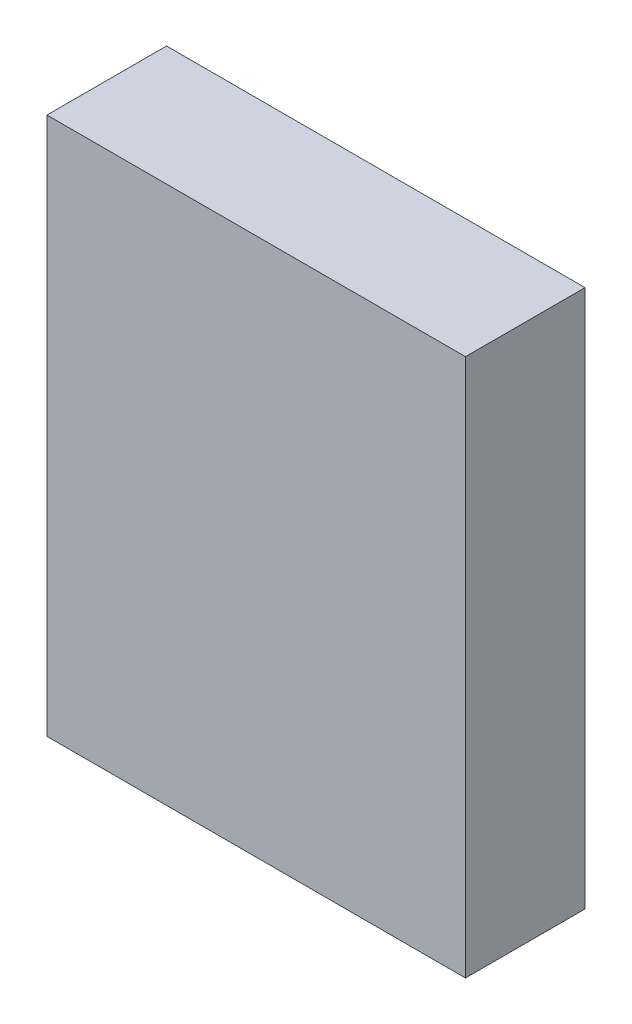
SolidWorks part; units mm, degrees
ref_plane "前视基准面" through (0, 0, 0) normal (0, 0, 1) x (1, 0, 0)
ref_plane "上视基准面" through (0, 0, 0) normal (0, 1, 0) x (1, 0, 0)
ref_plane "右视基准面" through (0, 0, 0) normal (1, 0, 0) x (0, 0, -1)
sketch "草图1" plane through (0, 0, 0) normal (0, 0, 1) x (1, 0, 0)
  line L1 (-35, -45) -> (35, -45)
  line L2 (-35, -45) -> (-35, 45)
  line L3 (-35, 45) -> (35, 45)
  line L4 (35, -45) -> (35, 45)
  line L5 (-35, -45) -> (35, 45) construction
  line L6 (-35, 45) -> (35, -45) construction
  point P0 (0, 0)
  dimension "D1" = 90
  dimension "D2" = 70
extrude "凸台-拉伸1" add sketch "草图1" along normal blind 20
